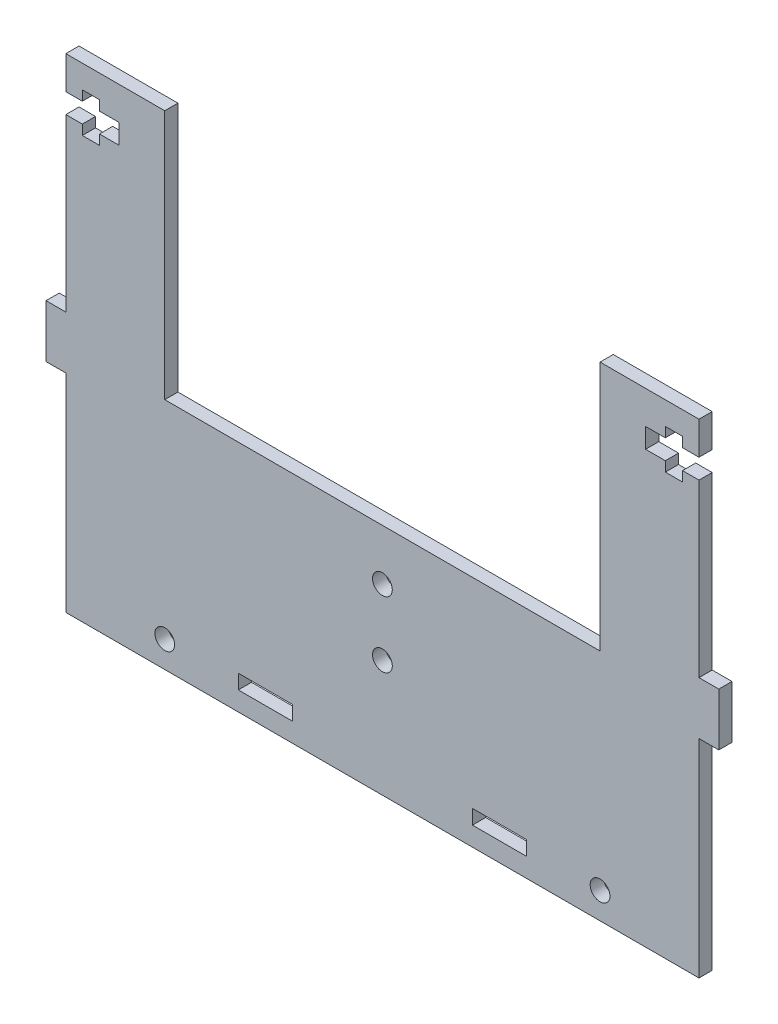
SolidWorks part; units mm, degrees
ref_plane "前视基准面" through (0, 0, 0) normal (0, 0, 1) x (1, 0, 0)
ref_plane "上视基准面" through (0, 0, 0) normal (0, 1, 0) x (1, 0, 0)
ref_plane "右视基准面" through (0, 0, 0) normal (1, 0, 0) x (0, 0, -1)
sketch "草图1" plane through (0, 0, 0) normal (0, 0, 1) x (1, 0, 0)
  line L0 (-47.7662, -53.1995) -> (-47.7662, -54.6995)
  line L1 (-24.1162, -115.6745) -> (-15.9162, -115.6745)
  line L2 (-15.9162, -113.4745) -> (-15.9162, -115.6745)
  line L3 (-24.1162, -113.4745) -> (-15.9162, -113.4745)
  line L4 (-24.1162, -113.4745) -> (-24.1162, -115.6745)
  line L5 (19.5838, -113.4745) -> (19.5838, -115.6745)
  line L6 (19.5838, -113.4745) -> (11.3838, -113.4745)
  line L7 (11.3838, -113.4745) -> (11.3838, -115.6745)
  line L10 (19.5838, -115.6745) -> (11.3838, -115.6745)
  line L12 (-42.1662, -50.1995) -> (-42.1662, -53.1995)
  line L15 (-47.7662, -50.1995) -> (-47.7662, -48.6995)
  line L16 (-50.2662, -79.137) -> (-53.2662, -79.137)
  line L17 (-53.2662, -79.137) -> (-53.2662, -87.137)
  line L18 (-53.2662, -87.137) -> (-50.2662, -87.137)
  line L19 (-50.2662, -87.137) -> (-50.2662, -118.5745)
  line L20 (-50.2662, -50.1995) -> (-47.7662, -50.1995)
  line L21 (-47.7662, -54.6995) -> (-45.1662, -54.6995)
  line L22 (-45.1662, -54.6995) -> (-45.1662, -53.1995)
  line L23 (-45.1662, -53.1995) -> (-42.1662, -53.1995)
  line L25 (-45.1662, -50.1995) -> (-42.1662, -50.1995)
  line L26 (-45.1662, -48.6995) -> (-45.1662, -50.1995)
  line L27 (-47.7662, -48.6995) -> (-45.1662, -48.6995)
  line L28 (-47.7662, -53.1995) -> (-50.2662, -53.1995)
  line L29 (-50.2662, -50.1995) -> (-50.2662, -53.1995) construction
  line L30 (-50.2662, -51.6995) -> (-48.6388, -51.6995) construction
  line L31 (-50.2662, -53.1995) -> (-50.2662, -79.137)
  line L60 (-50.2662, -45.1995) -> (-50.2662, -50.1995)
  line L62 (-2.2662, -100.8558) -> (-2.2662, -90.8558) construction
  line L68 (30.7338, -45.1995) -> (30.7338, -83.137)
  line L69 (30.7338, -83.137) -> (-35.2662, -83.137)
  line L70 (-35.2662, -83.137) -> (-35.2662, -45.1995)
  line L73 (-2.2662, -118.5745) -> (-2.2662, -83.137) construction
  line L74 (-2.2662, -118.5745) -> (-50.2662, -118.5745) construction
  line L75 (45.7338, -51.6995) -> (44.1065, -51.6995) construction
  line L76 (45.7338, -50.1995) -> (45.7338, -53.1995) construction
  line L77 (45.7338, -45.1995) -> (45.7338, -50.1995)
  line L78 (45.7338, -53.1995) -> (45.7338, -79.137)
  line L79 (43.2338, -53.1995) -> (45.7338, -53.1995)
  line L80 (43.2338, -48.6995) -> (40.6338, -48.6995)
  line L81 (40.6338, -48.6995) -> (40.6338, -50.1995)
  line L82 (40.6338, -50.1995) -> (37.6338, -50.1995)
  line L83 (40.6338, -53.1995) -> (37.6338, -53.1995)
  line L84 (40.6338, -54.6995) -> (40.6338, -53.1995)
  line L85 (43.2338, -54.6995) -> (40.6338, -54.6995)
  line L86 (45.7338, -50.1995) -> (43.2338, -50.1995)
  line L87 (45.7338, -87.137) -> (45.7338, -118.5745)
  line L88 (48.7338, -87.137) -> (45.7338, -87.137)
  line L89 (48.7338, -79.137) -> (48.7338, -87.137)
  line L90 (45.7338, -79.137) -> (48.7338, -79.137)
  line L91 (43.2338, -50.1995) -> (43.2338, -48.6995)
  line L92 (37.6338, -50.1995) -> (37.6338, -53.1995)
  line L93 (43.2338, -53.1995) -> (43.2338, -54.6995)
  line L94 (-50.2662, -45.1995) -> (-35.2662, -45.1995)
  line L95 (30.7338, -45.1995) -> (45.7338, -45.1995)
  line L96 (45.7338, -118.5745) -> (-50.2662, -118.5745)
  circle A0 centre (-35.2662, -114.5745) radius 1.5
  circle A1 centre (30.7338, -114.5745) radius 1.5
  circle A2 centre (-2.2662, -100.8558) radius 1.5
  circle A3 centre (-2.2662, -90.8558) radius 1.5
extrude "凸台-拉伸1" add sketch "草图1" along normal blind 2
